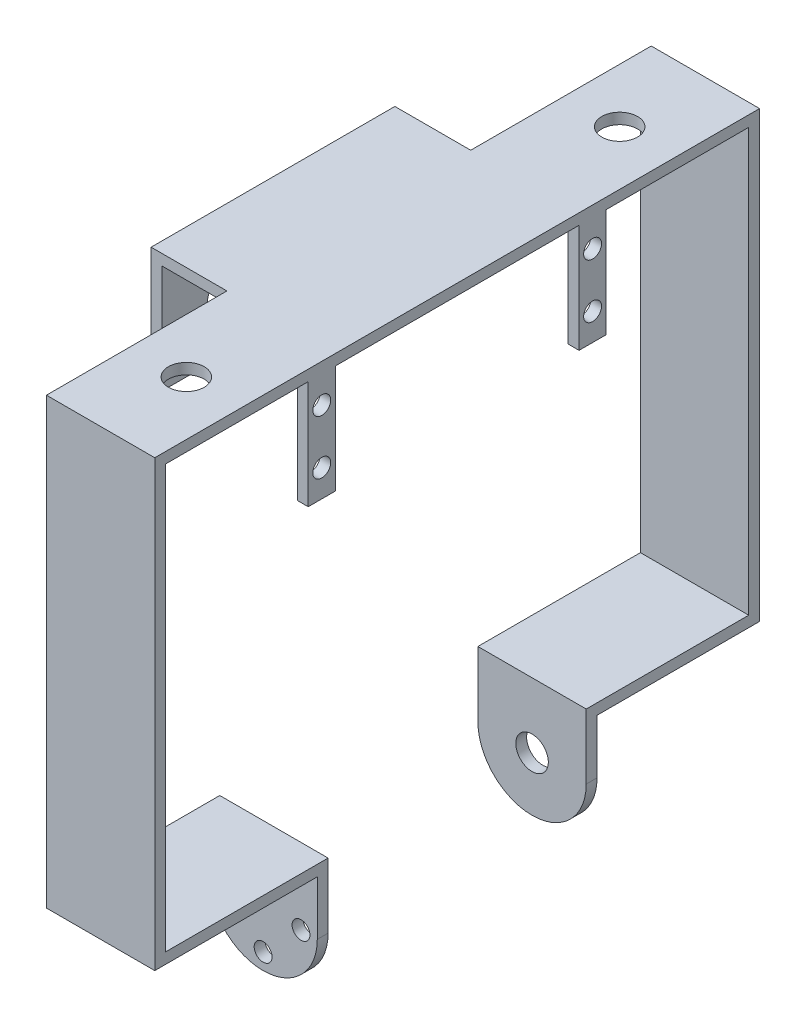
SolidWorks part; units mm, degrees
ref_plane "前视基准面" through (0, 0, 0) normal (0, 0, 1) x (1, 0, 0)
ref_plane "上视基准面" through (0, 0, 0) normal (0, 1, 0) x (1, 0, 0)
ref_plane "右视基准面" through (0, 0, 0) normal (1, 0, 0) x (0, 0, -1)
sketch "草图1" plane through (0, 0, 0) normal (0, 0, 1) x (1, 0, 0)
  line L2 (0, 0) -> (0, 12)
  line L3 (0, 12) -> (20, 12)
  line L4 (20, 0) -> (20, 12)
  arc A0 (0, 0) -> (20, 0) centre (10, 0) ccw
  dimension "D1" = 20
  dimension "D2" = 12
extrude "凸台-拉伸1" add sketch "草图1" along normal blind 2
sketch "草图2" plane through (0, 0, 2) normal (0, 0, 1) x (1, 0, 0)
  line L0 (0, 0) -> (20, 0) construction
  line L1 (10, 0) -> (10, -10) construction
  arc A0 (0, 0) -> (20, 0) centre (10, 0) ccw construction
  circle A1 centre (17, 0) radius 1.65
  circle A2 centre (10, -7) radius 1.65
  circle A3 centre (3, 0) radius 1.65
  circle A4 centre (10, 7) radius 1.65
  point P20 (10, 0)
  dimension "D2" = 3.3
  dimension "D1" = 7
  dimension "D3" = 4
extrude "切除-拉伸1" cut sketch "草图2" against normal blind 2
sketch "草图3" plane through (0, 0, 2) normal (0, 0, 1) x (1, 0, 0)
  line L0 (20, 0) -> (20, 12) construction
  line L1 (0, 12) -> (20, 12)
  line L2 (0, 12) -> (0, 10)
  line L3 (0, 10) -> (20, 10)
  line L4 (20, 12) -> (20, 10)
  dimension "D1" = 2
extrude "凸台-拉伸2" add sketch "草图3" along normal blind 30
sketch "草图4" plane through (0, 12, 0) normal (0, 1, 0) x (1, 0, 0)
  line L0 (20, -32) -> (20, 0) construction
  line L1 (0, -32) -> (20, -32)
  line L2 (0, -32) -> (0, -30)
  line L3 (0, -30) -> (20, -30)
  line L4 (20, -32) -> (20, -30)
  dimension "D1" = 2
extrude "凸台-拉伸3" add sketch "草图4" along normal blind 80
sketch "草图5" plane through (0, 0, 30) normal (0, 0, -1) x (-1, 0, 0)
  line L0 (0, 92) -> (0, 12) construction
  line L1 (-20, 92) -> (0, 92)
  line L2 (-20, 92) -> (-20, 90)
  line L3 (-20, 90) -> (0, 90)
  line L4 (0, 92) -> (0, 90)
  dimension "D1" = 2
extrude "凸台-拉伸4" add sketch "草图5" along normal blind 109.65
sketch "草图6" plane through (0, 90, 0) normal (0, -1, 0) x (1, 0, 0)
  line L0 (0, -79.65) -> (0, 30) construction
  line L1 (20, -79.65) -> (0, -79.65) construction
  line L2 (0, -79.65) -> (20, -79.65)
  line L3 (0, -79.65) -> (0, -77.65)
  line L4 (0, -77.65) -> (20, -77.65)
  line L5 (20, -79.65) -> (20, -77.65)
  line L6 (20, -79.65) -> (20, 30) construction
  dimension "D1" = 2
extrude "凸台-拉伸5" add sketch "草图6" along normal blind 80
sketch "草图7" plane through (0, 92, 0) normal (0, 1, 0) x (1, 0, 0)
  line L0 (0, 23.825) -> (20, 23.825) construction
  line L1 (0, 79.65) -> (0, -32) construction
  line L2 (20, -32) -> (20, 79.65) construction
ref_plane "基准面1" through (0, 0, -23.825) normal (0, 0, 1) x (1, 0, 0)
mirror "镜向2" about plane through (0, 0, -23.825) normal (0, 0, 1) of "切除-拉伸1", "凸台-拉伸1", "凸台-拉伸2"
mirror "镜向3" about plane through (0, 0, -23.825) normal (0, 0, 1) of "凸台-拉伸1"
sketch "草图8" plane through (0, 0, -49.65) normal (0, 0, -1) x (-1, 0, 0)
  line L0 (-20, 0) -> (0, 0) construction
  circle A0 centre (-10, 0) radius 3
  dimension "D1" = 6
extrude "切除-拉伸2" cut sketch "草图8" against normal up to next
sketch "草图9" plane through (0, 90, 0) normal (0, -1, 0) x (1, 0, 0)
  line L0 (20, -77.65) -> (20, 30) construction
  line L1 (18, -1.325) -> (20, -1.325)
  line L2 (18, -1.325) -> (18, 3.675)
  line L3 (18, 3.675) -> (20, 3.675)
  line L4 (20, -1.325) -> (20, 3.675)
  line L5 (18, -1.325) -> (20, 3.675) construction
  line L6 (18, 3.675) -> (20, -1.325) construction
  line L7 (0, -23.825) -> (20, -23.825) construction
  line L8 (11, -23.825) -> (-11, -23.825) construction
  line L9 (18, -46.325) -> (20, -46.325)
  line L10 (18, -51.325) -> (20, -51.325)
  line L11 (20, -46.325) -> (20, -51.325)
  line L12 (18, -46.325) -> (18, -51.325)
  point P0 (19, 1.175)
  dimension "D1" = 25
  dimension "D2" = 5
  dimension "D3" = 2
extrude "凸台-拉伸6" add sketch "草图9" along normal blind 20
sketch "草图10" plane through (20, 0, 0) normal (1, 0, 0) x (0, 0, -1)
  line L0 (-1.175, 70) -> (-1.175, 92) construction
  line L1 (1.325, 70) -> (-3.675, 70) construction
  line L2 (-32, 92) -> (79.65, 92) construction
  line L3 (23.825, 11) -> (23.825, -11) construction
  circle A0 centre (-1.175, 75) radius 1.65
  circle A1 centre (-1.175, 85) radius 1.65
  circle A2 centre (48.825, 75) radius 1.65
  circle A3 centre (48.825, 85) radius 1.65
  dimension "D2" = 3.3
  dimension "D3" = 3.3
  dimension "D1" = 10
  dimension "D4" = 5
extrude "切除-拉伸3" cut sketch "草图10" against normal blind 20
sketch "草图11" plane through (0, 92, 0) normal (0, 1, 0) x (1, 0, 0)
  line L0 (10, 79.65) -> (10, -32) construction
  line L1 (0, 79.65) -> (20, 79.65) construction
  line L2 (0, -32) -> (20, -32) construction
  line L3 (0, 23.825) -> (20, 23.825) construction
  line L4 (-11, 23.825) -> (11, 23.825) construction
  circle A0 centre (10, 63.825) radius 3.3
  circle A1 centre (10, -16.175) radius 3.3
  dimension "D1" = 6.6
  dimension "D2" = 40
extrude "切除-拉伸4" cut sketch "草图11" against normal blind 10
sketch "草图12" plane through (0, 0, 0) normal (-1, 0, 0) x (0, 0, 1)
  line L0 (-79.65, 92) -> (32, 92) construction
  line L1 (-46.325, 90) -> (-1.325, 90)
  line L2 (-46.325, 90) -> (-46.325, 92)
  line L3 (-46.325, 92) -> (-1.325, 92)
  line L4 (-1.325, 90) -> (-1.325, 92)
  dimension "D1" = 45
extrude "凸台-拉伸7" add sketch "草图12" along normal blind 14
sketch "草图13" plane through (0, 90, 0) normal (0, -1, 0) x (1, 0, 0)
  line L0 (-14, -46.325) -> (0, -46.325) construction
  line L1 (-14, -1.325) -> (-12, -1.325)
  line L2 (-14, -1.325) -> (-14, -46.325)
  line L3 (-14, -46.325) -> (-12, -46.325)
  line L4 (-12, -1.325) -> (-12, -46.325)
  dimension "D1" = 2
extrude "凸台-拉伸8" add sketch "草图13" along normal blind 20
sketch "草图14" plane through (-14, 0, 0) normal (-1, 0, 0) x (0, 0, 1)
  line L0 (-1.325, 70) -> (-1.325, 90) construction
  line L2 (-1.325, 92) -> (-46.325, 92) construction
  circle A0 centre (-12.725, 80) radius 3
  dimension "D3" = 6
  dimension "D1" = 11.4
  dimension "D2" = 12
extrude "切除-拉伸6" cut sketch "草图14" against normal blind 20
